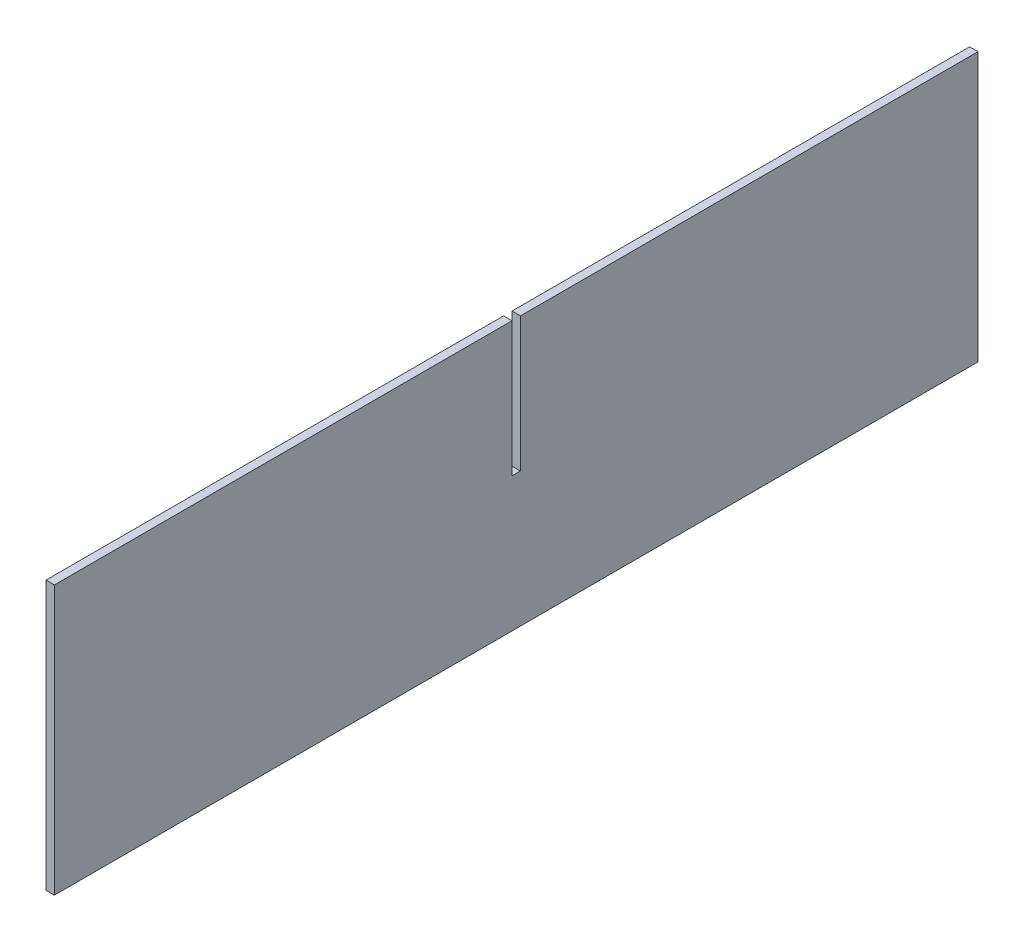
SolidWorks part; units mm, degrees
material "Mahogany"
ref_plane "Front Plane" through (0, 0, 0) normal (0, 0, 1) x (1, 0, 0)
ref_plane "Top Plane" through (0, 0, 0) normal (0, 1, 0) x (1, 0, 0)
ref_plane "Right Plane" through (0, 0, 0) normal (1, 0, 0) x (0, 0, -1)
sketch "Sketch1" plane through (0, 0, 0) normal (1, 0, 0) x (0, 0, -1)
  line L0 (-137.5, -40) -> (137.5, -40)
  line L1 (-137.5, -40) -> (137.5, -40) construction
  line L2 (-137.5, -40) -> (-137.5, 40)
  line L3 (-137.5, 40) -> (137.5, 40) construction
  line L4 (137.5, -40) -> (137.5, 40)
  line L5 (-137.5, -40) -> (137.5, 40) construction
  line L6 (-137.5, 40) -> (137.5, -40) construction
  line L7 (137.5, -40) -> (1.25, -40) construction
  line L11 (-137.5, 40) -> (-1.25, 40)
  line L12 (-1.25, 0) -> (1.25, 0)
  line L13 (1.25, 40) -> (137.5, 40)
  line L14 (-1.25, 0) -> (-1.25, 40)
  line L15 (-1.25, 40) -> (1.25, 40) construction
  line L16 (1.25, 0) -> (1.25, 40)
  line L17 (-1.25, 0) -> (1.25, 40) construction
  line L18 (-1.25, 40) -> (1.25, 0) construction
  point P0 (0, 0)
  point P6 (0, 20)
  dimension "D1" = 275
  dimension "D2" = 80
  dimension "D3" = 2.5
extrude "Boss-Extrude1" add sketch "Sketch1" along normal mid plane 2.5
